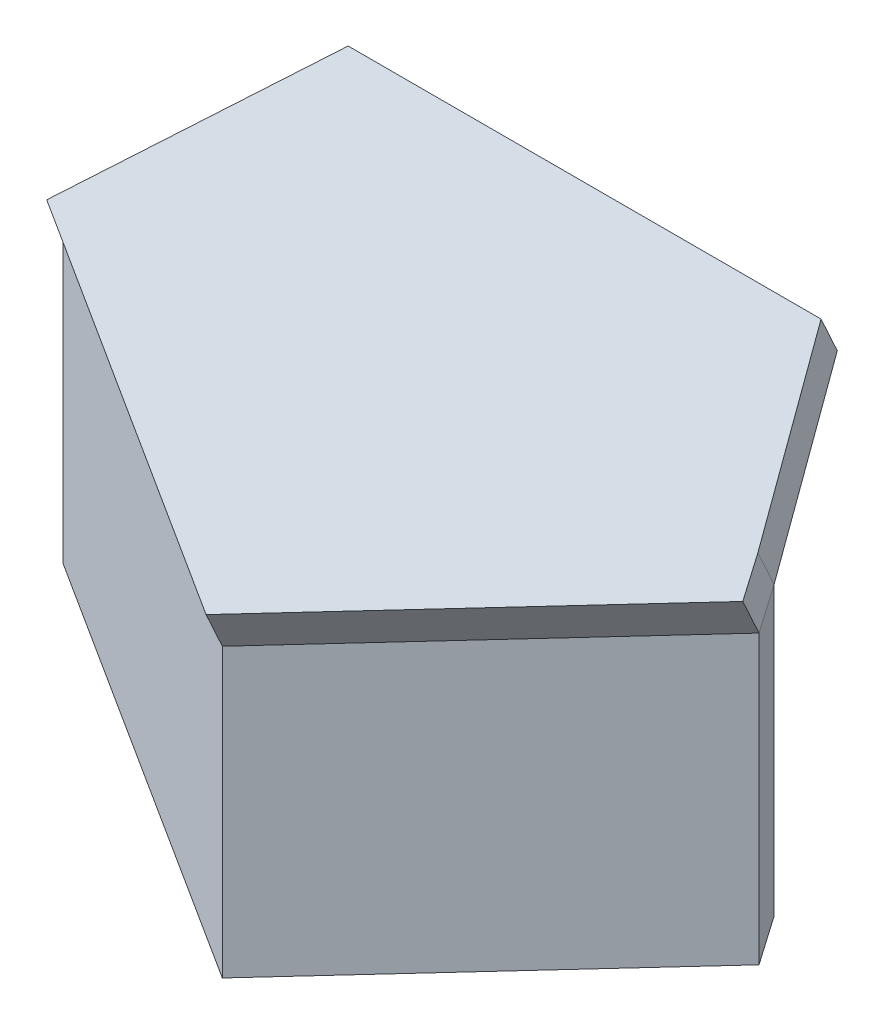
SolidWorks part; units mm, degrees
ref_plane "前视基准面" through (0, 0, 0) normal (0, 0, 1) x (1, 0, 0)
ref_plane "上视基准面" through (0, 0, 0) normal (0, 1, 0) x (1, 0, 0)
ref_plane "右视基准面" through (0, 0, 0) normal (1, 0, 0) x (0, 0, -1)
sketch "草图5" plane through (0, 0, 0) normal (0, 1, 0) x (1, 0, 0)
  line L0 (-85.1138, 46.4974) -> (0, 0)
  line L1 (0, 0) -> (83.4164, 46.4974)
extrude "拉伸-薄壁2" add sketch "草图5" along normal blind 100 thin
sketch "草图6" plane through (0, 0, 0) normal (1, 0, 0) x (0, 0, -1)
  line L0 (-11.4215, 0) -> (46.4974, 26.438)
  line L1 (46.4974, 100) -> (46.4974, 0) construction
  line L2 (46.4974, 26.438) -> (46.4974, 0)
  line L3 (46.4974, 0) -> (-11.4215, 0)
  line L4 (46.4974, 100) -> (-11.4215, 73.562)
  line L5 (-11.4215, 100) -> (-11.4215, 0) construction
  line L6 (-11.4215, 73.562) -> (-11.4215, 100)
  line L7 (-11.4215, 100) -> (46.4974, 100)
extrude "切除-拉伸1" cut sketch "草图6" against normal through all and the other way through all
sketch "草图7" plane through (0, 65.1921, 29.7579) normal (0, 0.9097, 0.4152) x (1, 0, 0)
  line L0 (88.2852, 74.2224) -> (83.4164, 83.824) construction
  line L1 (-85.1138, 83.824) -> (-89.9081, 74.1771) construction
  line L2 (88.2852, 74.2224) -> (0.0487, 20.1564) construction
  line L3 (0.0487, 20.1564) -> (-89.9081, 74.1771) construction
  line L4 (88.2852, 74.2224) -> (83.4164, 83.824)
  line L5 (-85.1138, 83.824) -> (-89.9081, 74.1771)
  line L6 (88.2852, 74.2224) -> (0.0487, 20.1564)
  line L7 (0.0487, 20.1564) -> (-89.9081, 74.1771)
  line L8 (-85.1138, 83.824) -> (-62.6399, 129.046)
  line L9 (83.4164, 83.824) -> (58.456, 129.046)
  line L10 (58.456, 129.046) -> (-62.6399, 129.046)
extrude "凸台-拉伸3" add sketch "草图7" along normal blind 10
